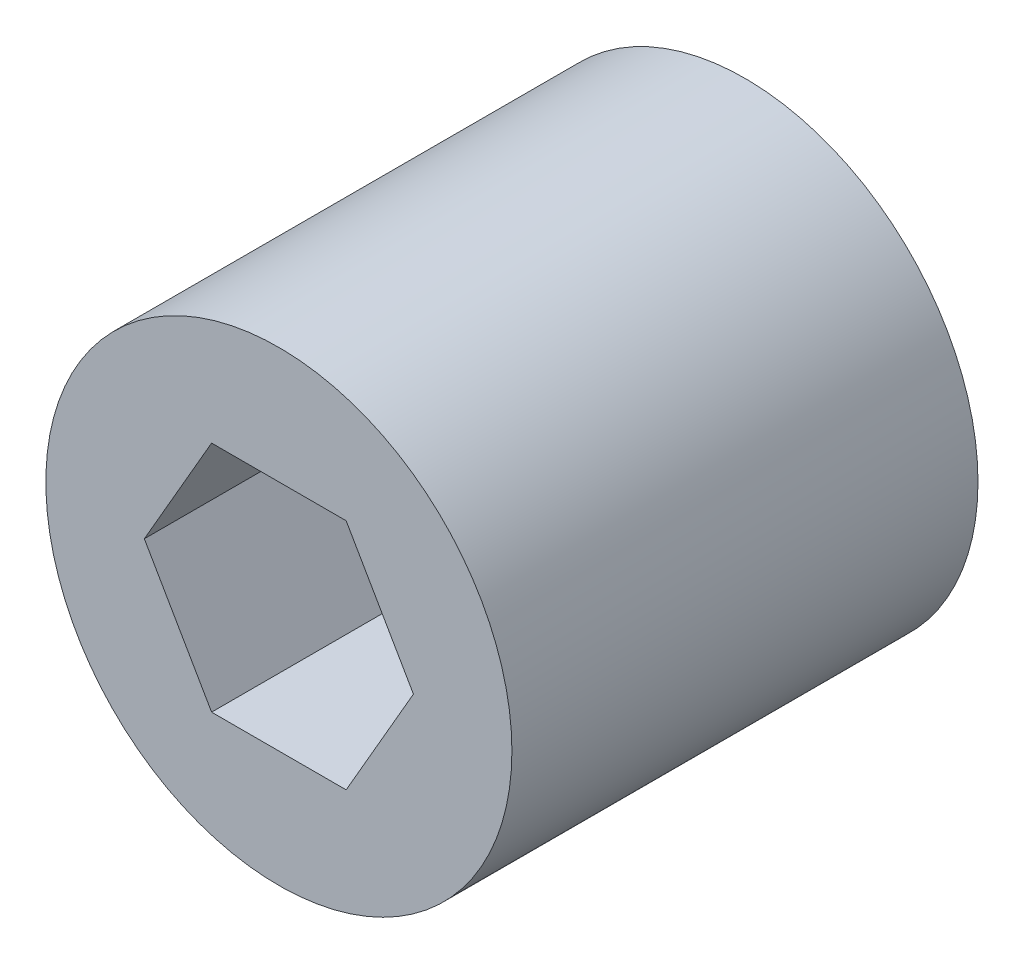
SolidWorks part; units mm, degrees
ref_plane "Front Plane" through (0, 0, 0) normal (0, 0, 1) x (1, 0, 0)
ref_plane "Top Plane" through (0, 0, 0) normal (0, 1, 0) x (1, 0, 0)
ref_plane "Right Plane" through (0, 0, 0) normal (1, 0, 0) x (0, 0, -1)
sketch "S01 - M3 headless body" plane through (0, 0, 0) normal (0, 0, 1) x (1, 0, 0)
  circle A0 centre (0, 0) radius 1.5
  dimension "D1" = 3
extrude "01 - M3 headless body" add sketch "S01 - M3 headless body" along normal blind 4
sketch "S02 - 1.5 mm hex socket" plane through (0, 0, 0) normal (0, 0, 1) x (1, 0, 0)
  line L0 (0.866, 0) -> (0.433, 0.75)
  line L1 (0.433, 0.75) -> (-0.433, 0.75)
  line L2 (-0.433, 0.75) -> (-0.866, 0)
  line L3 (-0.866, 0) -> (-0.433, -0.75)
  line L4 (-0.433, -0.75) -> (0.433, -0.75)
  line L5 (0.433, -0.75) -> (0.866, 0)
  dimension "D1" = 0.433
  dimension "D2" = 0.866
  dimension "D3" = 0.433
  dimension "D4" = 0.866
  dimension "D5" = 0.75
  dimension "D6" = 0.75
extrude "02 - 1.5 mm hex socket" cut sketch "S02 - 1.5 mm hex socket" along normal blind 1.3 from offset 2.8
sketch "Three millimetre screw length layout" plane through (0, 0, 0) normal (0, 0, 1) x (1, 0, 0)
  circle A0 centre (0, 0) radius 2
extrude "Three millimetre screw length" cut sketch "Three millimetre screw length layout" against normal blind 1.1 from offset 1
